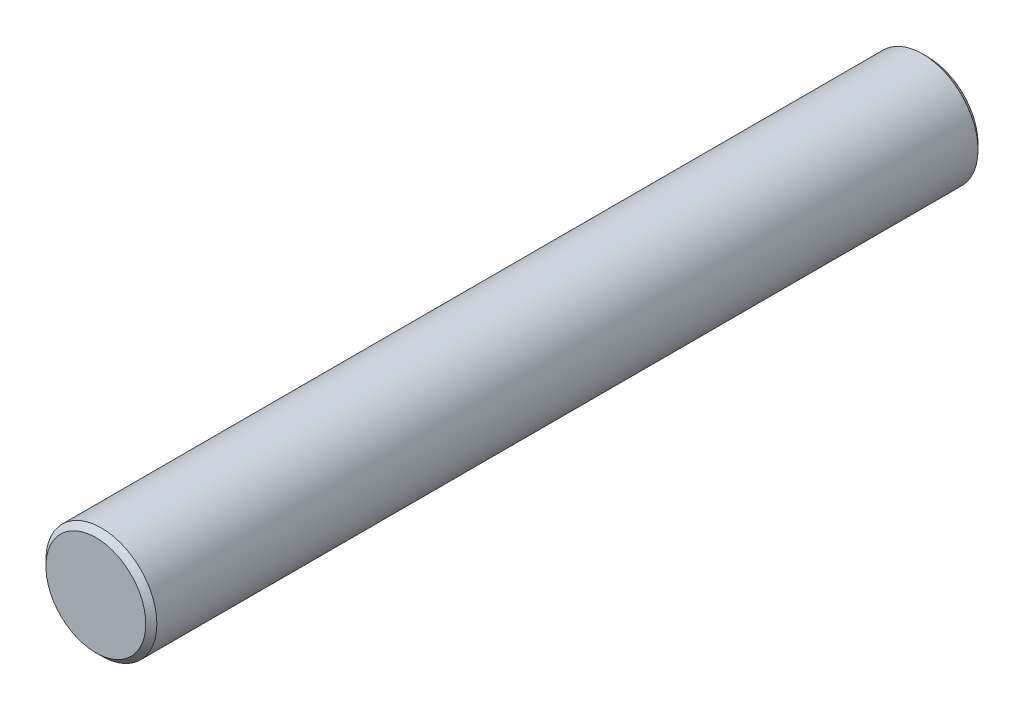
SolidWorks part; units mm, degrees
ref_plane "前视基准面" through (0, 0, 0) normal (0, 0, 1) x (1, 0, 0)
ref_plane "上视基准面" through (0, 0, 0) normal (0, 1, 0) x (1, 0, 0)
ref_plane "右视基准面" through (0, 0, 0) normal (1, 0, 0) x (0, 0, -1)
sketch "草图1" plane through (0, 0, 0) normal (0, 0, 1) x (1, 0, 0)
  circle A0 centre (0, 0) radius 2
extrude "凸台-拉伸1" add sketch "草图1" along normal blind 30
chamfer "倒角1" distance 0.2 angle 45 2 edges at (2, 0, 0) (2, 0, 30)
